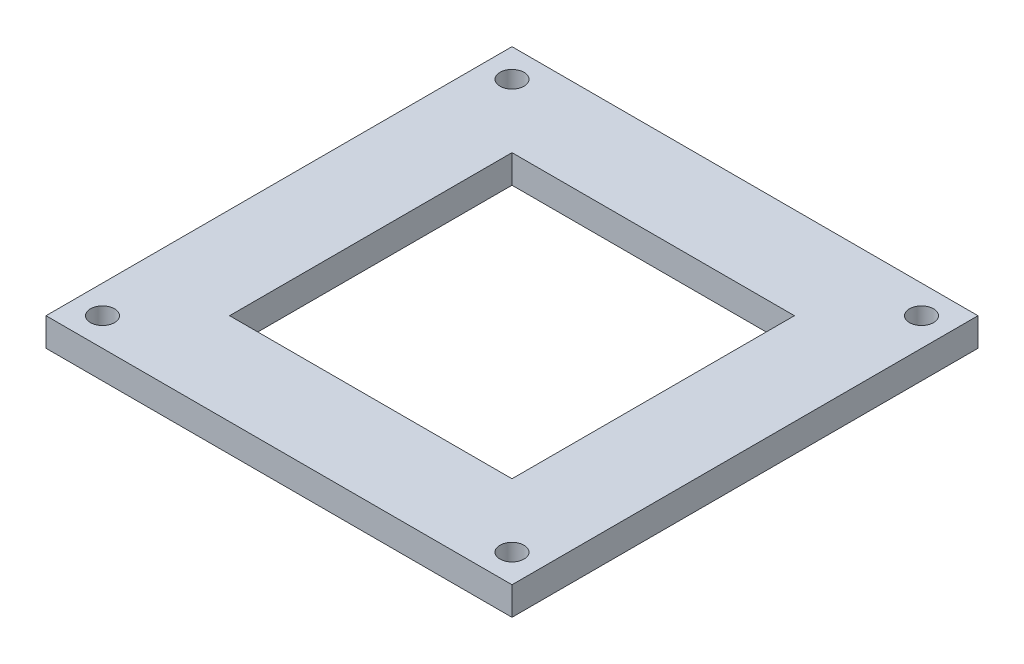
SolidWorks part; units mm, degrees
ref_plane "Front Plane" through (0, 0, 0) normal (0, 0, 1) x (1, 0, 0)
ref_plane "Top Plane" through (0, 0, 0) normal (0, 1, 0) x (1, 0, 0)
ref_plane "Right Plane" through (0, 0, 0) normal (1, 0, 0) x (0, 0, -1)
sketch "Sketch1" plane through (0, 0, 0) normal (0, 1, 0) x (1, 0, 0)
  line L1 (-33, -33) -> (33, -33)
  line L2 (-33, -33) -> (-33, 33)
  line L3 (-33, 33) -> (33, 33)
  line L4 (33, -33) -> (33, 33)
  line L5 (-33, -33) -> (33, 33) construction
  line L6 (-33, 33) -> (33, -33) construction
  line L7 (-20, -20) -> (20, -20)
  line L8 (-20, -20) -> (-20, 20)
  line L9 (-20, 20) -> (20, 20)
  line L10 (20, -20) -> (20, 20)
  line L11 (-20, -20) -> (20, 20) construction
  line L12 (-20, 20) -> (20, -20) construction
  circle A0 centre (-29, 29) radius 1.705
  circle A1 centre (29, 29) radius 1.705
  circle A2 centre (29, -29) radius 1.705
  circle A3 centre (-29, -29) radius 1.705
  point P0 (0, 0)
  point P6 (0, 0)
  dimension "D1" = 3.41
  dimension "D2" = 4
  dimension "D4" = 4
  dimension "D6" = 4
  dimension "D3" = 40
  dimension "D5" = 4
  dimension "D7" = 13
  dimension "D8" = 13
extrude "Boss-Extrude1" add sketch "Sketch1" along normal blind 4
